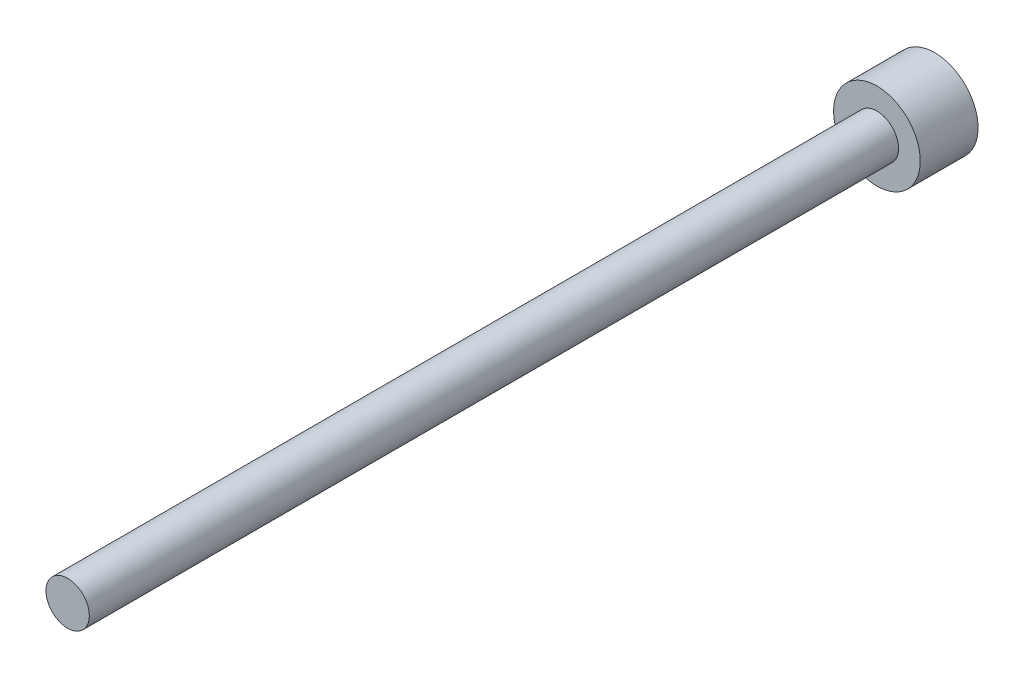
SolidWorks part; units mm, degrees
ref_plane "Front Plane" through (0, 0, 0) normal (0, 0, 1) x (1, 0, 0)
ref_plane "Top Plane" through (0, 0, 0) normal (0, 1, 0) x (1, 0, 0)
ref_plane "Right Plane" through (0, 0, 0) normal (1, 0, 0) x (0, 0, -1)
sketch "Sketch1" plane through (0, 0, 0) normal (0, 0, 1) x (1, 0, 0)
  circle A0 centre (0, 0) radius 2.3813
  dimension "D1" = 4.7625
extrude "Boss-Extrude1" add sketch "Sketch1" along normal blind 88.9
sketch "Sketch2" plane through (0, 0, 0) normal (0, 0, -1) x (-1, 0, 0)
  circle A0 centre (0, 0) radius 4.7625
  dimension "D1" = 9.525
extrude "Boss-Extrude2" add sketch "Sketch2" along normal blind 6.35
